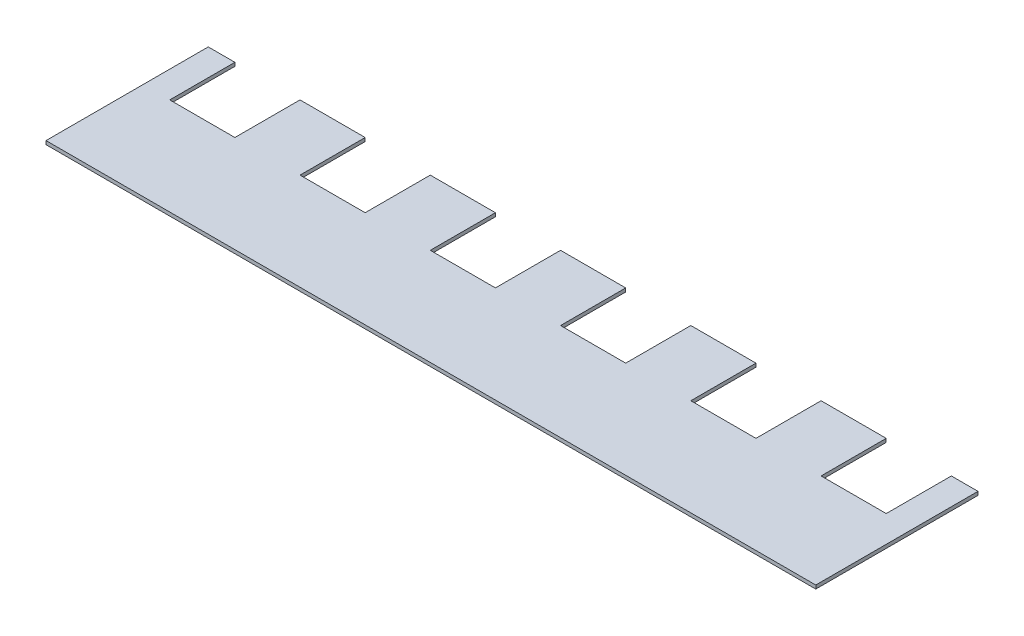
SolidWorks part; units mm, degrees
ref_plane "Front Plane" through (0, 0, 0) normal (0, 0, 1) x (1, 0, 0)
ref_plane "Top Plane" through (0, 0, 0) normal (0, 1, 0) x (1, 0, 0)
ref_plane "Right Plane" through (0, 0, 0) normal (1, 0, 0) x (0, 0, -1)
sketch "Sketch1" plane through (0, 0, 0) normal (0, 1, 0) x (1, 0, 0)
  line L1 (-62.5127, 109.9831) -> (587.4873, 109.9831)
  line L2 (-62.5127, 109.9831) -> (-62.5127, -27.0169)
  line L3 (-62.5127, -27.0169) -> (587.4873, -27.0169)
  line L4 (587.4873, 109.9831) -> (587.4873, -27.0169)
  line L5 (-40.0127, 109.9831) -> (14.9873, 109.9831)
  line L6 (-40.0127, 109.9831) -> (-40.0127, 54.9831)
  line L7 (-40.0127, 54.9831) -> (14.9873, 54.9831)
  line L8 (14.9873, 109.9831) -> (14.9873, 54.9831)
  dimension "D1" = 650
  dimension "D2" = 137
  dimension "D3" = 0
  dimension "D4" = 55
  dimension "D5" = 55
  dimension "D6" = 22.5
sketch "Sketch2" plane through (0, 0, 0) normal (0, 1, 0) x (1, 0, 0)
  line L0 (-62.5127, 109.9831) -> (587.4873, 109.9831) construction
  line L1 (69.9873, 109.9831) -> (124.9873, 109.9831)
  line L2 (69.9873, 109.9831) -> (69.9873, 54.9831)
  line L3 (69.9873, 54.9831) -> (124.9873, 54.9831)
  line L4 (124.9873, 109.9831) -> (124.9873, 54.9831)
  line L5 (14.9873, 109.9831) -> (14.9873, 54.9831) construction
  line L7 (179.9873, 109.9831) -> (234.9873, 109.9831)
  line L8 (179.9873, 109.9831) -> (179.9873, 54.9831)
  line L9 (179.9873, 54.9831) -> (234.9873, 54.9831)
  line L10 (234.9873, 109.9831) -> (234.9873, 54.9831)
  line L11 (289.9873, 109.9831) -> (344.9873, 109.9831)
  line L12 (289.9873, 109.9831) -> (289.9873, 54.9831)
  line L13 (289.9873, 54.9831) -> (344.9873, 54.9831)
  line L14 (344.9873, 109.9831) -> (344.9873, 54.9831)
  line L15 (399.9873, 109.9831) -> (454.9873, 109.9831)
  line L16 (399.9873, 109.9831) -> (399.9873, 54.9831)
  line L17 (399.9873, 54.9831) -> (454.9873, 54.9831)
  line L18 (454.9873, 109.9831) -> (454.9873, 54.9831)
  line L19 (509.9873, 109.9831) -> (564.9873, 109.9831)
  line L20 (509.9873, 109.9831) -> (509.9873, 54.9831)
  line L21 (509.9873, 54.9831) -> (564.9873, 54.9831)
  line L22 (564.9873, 109.9831) -> (564.9873, 54.9831)
  dimension "D1" = 0
  dimension "D2" = 55
  dimension "D3" = 55
  dimension "D4" = 55
  dimension "D5" = 0
  dimension "D6" = 55
  dimension "D7" = 55
  dimension "D8" = 55
  dimension "D9" = 0
  dimension "D10" = 55
  dimension "D11" = 55
  dimension "D12" = 55
  dimension "D13" = 0
  dimension "D14" = 55
  dimension "D15" = 55
  dimension "D16" = 55
  dimension "D17" = 0
  dimension "D18" = 55
  dimension "D19" = 55
  dimension "D20" = 55
extrude "Boss-Extrude1" add sketch "Sketch1" along normal blind 3 contours L3 L4 L1 L2
extrude "Cut-Extrude2" cut sketch "Sketch2" against normal through all and the other way through all contours L11 L14 L13 L12 | L7 L10 L9 L8 | L3 L4 L1 L2 | L19 L22 L21 L20 | L15 L18 L17 L16
sketch "Sketch3" plane through (0, 3, 0) normal (0, 1, 0) x (1, 0, 0)
  line L0 (69.9873, 109.9831) -> (69.9873, 54.9831) construction
  line L1 (-40.0127, 109.9831) -> (14.9873, 109.9831)
  line L2 (-40.0127, 109.9831) -> (-40.0127, 54.9831)
  line L3 (-40.0127, 54.9831) -> (14.9873, 54.9831)
  line L4 (14.9873, 109.9831) -> (14.9873, 54.9831)
  line L5 (-62.5127, 109.9831) -> (69.9873, 109.9831) construction
  dimension "D1" = 55
  dimension "D2" = 55
  dimension "D3" = 55
  dimension "D4" = 0
  dimension "D5" = 55
  dimension "D6" = 55
extrude "Cut-Extrude3" cut sketch "Sketch3" against normal through all
